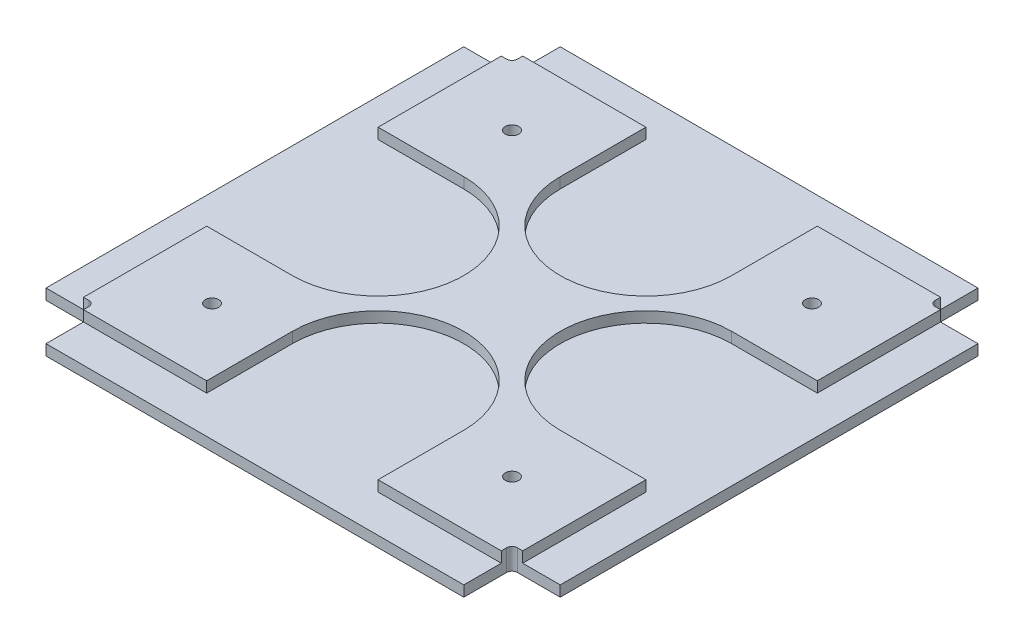
SolidWorks part; units mm, degrees
material "6061 Alloy"
ref_plane "Front Plane" through (0, 0, 0) normal (0, 0, 1) x (1, 0, 0)
ref_plane "Top Plane" through (0, 0, 0) normal (0, 1, 0) x (1, 0, 0)
ref_plane "Right Plane" through (0, 0, 0) normal (1, 0, 0) x (0, 0, -1)
sketch "Sketch1" plane through (0, 0, 0) normal (0, 1, 0) x (1, 0, 0)
  line L0 (0, 9) -> (8, 9)
  line L1 (9, 8) -> (9, 0)
  line L2 (9, 0) -> (87, 0)
  line L3 (87, 0) -> (87, 8)
  line L4 (88, 9) -> (96, 9)
  line L5 (96, 9) -> (96, 87)
  line L6 (96, 87) -> (88, 87)
  line L7 (87, 88) -> (87, 96)
  line L8 (87, 96) -> (9, 96)
  line L9 (9, 96) -> (9, 88)
  line L10 (8, 87) -> (0, 87)
  line L11 (0, 87) -> (0, 9)
  arc A0 (8, 9) -> (9, 8) centre (8, 8) cw
  arc A1 (87, 8) -> (88, 9) centre (88, 8) cw
  arc A2 (88, 87) -> (87, 88) centre (88, 88) cw
  arc A3 (9, 88) -> (8, 87) centre (8, 88) cw
  point P15 (9, 9)
  dimension "D3" = 1
  dimension "D1" = 96
  dimension "D2" = 9
extrude "Base" add sketch "Sketch1" along normal blind 2
sketch "Sketch2" plane through (0, 2, 0) normal (0, 1, 0) x (1, 0, 0)
  line L2 (32, 89) -> (32, 73)
  line L3 (32, 89) -> (9, 89)
  line L4 (9, 89) -> (9, 88)
  line L5 (8, 87) -> (7, 87)
  line L6 (7, 87) -> (7, 64)
  line L7 (7, 64) -> (23, 64)
  line L8 (87, 96) -> (9, 96) construction
  line L11 (48, 73) -> (48, 57) construction
  line L12 (39, 48) -> (23, 48) construction
  line L13 (89, 64) -> (73, 64)
  line L14 (89, 87) -> (89, 64)
  line L15 (88, 87) -> (89, 87)
  line L16 (87, 89) -> (87, 88)
  line L17 (64, 89) -> (87, 89)
  line L18 (64, 89) -> (64, 73)
  line L19 (64, 7) -> (64, 23)
  line L20 (64, 7) -> (87, 7)
  line L21 (87, 7) -> (87, 8)
  line L22 (88, 9) -> (89, 9)
  line L23 (89, 9) -> (89, 32)
  line L24 (89, 32) -> (73, 32)
  line L25 (7, 32) -> (23, 32)
  line L26 (7, 9) -> (7, 32)
  line L27 (8, 9) -> (7, 9)
  line L30 (9, 7) -> (9, 8)
  line L31 (32, 7) -> (9, 7)
  line L34 (32, 7) -> (32, 23)
  arc A0 (32, 73) -> (64, 73) centre (48, 73) ccw
  arc A1 (9, 88) -> (8, 87) centre (8, 88) cw
  arc A2 (23, 64) -> (23, 32) centre (23, 48) cw
  arc A3 (8, 87) -> (9, 88) centre (8, 88) ccw construction
  arc A4 (73, 64) -> (73, 32) centre (73, 48) ccw
  arc A5 (87, 88) -> (88, 87) centre (88, 88) ccw
  arc A6 (87, 8) -> (88, 9) centre (88, 8) cw
  arc A7 (9, 8) -> (8, 9) centre (8, 8) ccw
  arc A9 (32, 23) -> (64, 23) centre (48, 23) cw
  point P18 (48, 96)
  dimension "D2" = 16
  dimension "D1" = 7
  dimension "D3" = 16
extrude "Antenna Storage" add sketch "Sketch2" along normal blind 2
hole_wizard "M3x0.5 Tapped Holes For Mounting" positions "Sketch4" profile "Sketch3" tap size "M3x0.5" standard "Ansi Metric" end condition through all
sketch "Sketch4" plane through (0, 4, 0) normal (0, 1, 0) x (-1, 0, 0)
  line L4 (-96, -9) -> (-96, -87) construction
  line L5 (-87, -96) -> (-9, -96) construction
  line L6 (-9, 0) -> (-87, 0) construction
  line L7 (0, -87) -> (0, -9) construction
  point P1 (-20, -20)
  point P5 (-20, -76)
  point P7 (-76, -20)
  point P9 (-76, -76)
  dimension "D1" = 20
  dimension "D2" = 20
  dimension "D3" = 20
  dimension "D4" = 20
sketch "Sketch3" plane through (20, 4, -20) normal (1, 0, 0) x (0, 0, 1)
  line L0 (0, 0) -> (0, 4)
  line L1 (0, 4) -> (1.25, 4)
  line L2 (1.25, 4) -> (1.25, 0)
  line L5 (1.25, 0) -> (0, 0)
  line L11 (0, -6.35) -> (0, 107.95) construction
  dimension "Thru Tap Drill Dia." = 2.5
  dimension "Thru Tap Drill Depth" = 4
cosmetic thread "Hole Thread1" parameters "D2"=3
cosmetic thread "Hole Thread2" parameters "D2"=3
cosmetic thread "Hole Thread3" parameters "D2"=3
cosmetic thread "Hole Thread4" parameters "D2"=3
